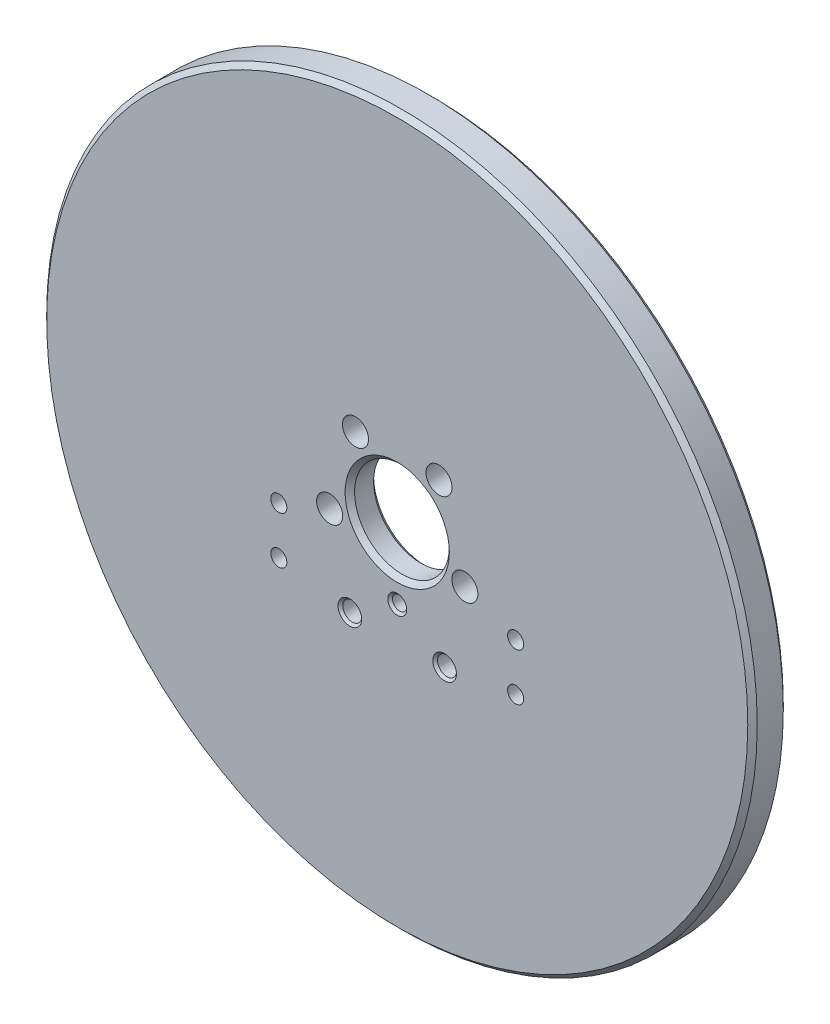
SolidWorks part; units mm, degrees
material "Q235"
ref_plane "前视基准面" through (0, 0, 0) normal (0, 0, 1) x (1, 0, 0)
ref_plane "上视基准面" through (0, 0, 0) normal (0, 1, 0) x (1, 0, 0)
ref_plane "右视基准面" through (0, 0, 0) normal (1, 0, 0) x (0, 0, -1)
ref_plane "基准面1" through (0, 0, 1) normal (0, 0, 1) x (1, 0, 0)
sketch "草图2" plane through (0, 0, 1) normal (0, 0, 1) x (1, 0, 0)
  circle A1 centre (18.5566, -25.5225) radius 150
  dimension "D1" = 300
extrude "凸台-拉伸1" add sketch "草图2" along normal blind 15
sketch "草图3" plane through (0, 0, 1) normal (0, 0, -1) x (-1, 0, 0)
  circle A0 centre (-18.5566, -25.5225) radius 35
  dimension "D1" = 70
extrude "切除-拉伸1" cut sketch "草图3" against normal blind 3
sketch "草图4" plane through (0, 0, 1) normal (0, 0, -1) x (-1, 0, 0)
  circle A0 centre (-18.5566, -25.5225) radius 35 construction
  circle A1 centre (-18.5566, -25.5225) radius 35
  circle A2 centre (-18.5566, -25.5225) radius 38.5
  dimension "D1" = 77
extrude "凸台-拉伸2" add sketch "草图4" along normal up to surface (16.5 mm away)
sketch "草图5" plane through (0, 0, 1) normal (0, 0, -1) x (-1, 0, 0)
  circle A0 centre (-18.5566, -25.5225) radius 38.5 construction
  circle A1 centre (-18.5566, -25.5225) radius 38.5
  circle A2 centre (-18.5566, -25.5225) radius 46.5
  dimension "D1" = 8
extrude "凸台-拉伸3" add sketch "草图5" along normal offset from surface (13.5 mm away) 3
chamfer "倒角1" distance 0.5 angle 45 2 edges at (18.5566, 12.9775, -15.5) (18.5566, 9.4775, -15.5)
hole_wizard "打孔尺寸根据内六角圆柱头螺钉的类型1" positions "草图8" profile "草图7" counterbore size "M6" standard "GB"
sketch "草图8" plane through (42.6264, -13.4634, 16) normal (0, 0, 1) x (1, 0, 0)
  line L0 (-24.0698, -12.0592) -> (-24.0698, 17.9408) construction
  line L2 (-24.0698, -12.0592) -> (-41.7034, 12.2114) construction
  line L3 (-24.0698, -12.0592) -> (-52.6015, -21.3297) construction
  line L6 (-24.0698, -12.0592) -> (4.4619, -21.3297) construction
  line L9 (-6.4362, 12.2114) -> (-24.0698, -12.0592) construction
  circle A0 centre (-24.0698, -12.0592) radius 30 construction
  circle A1 centre (-24.0698, -12.0592) radius 150 construction
  point P0 (-41.7034, 12.2114)
  point P45 (-6.4362, 12.2114)
  point P46 (4.4619, -21.3297)
  point P48 (-52.6015, -21.3297)
  point P50 (-24.0698, -42.0592) [skipped]
  dimension "D1" = 60
  dimension "D2" = 36
  dimension "D4" = 72
  dimension "D5" = 72
  dimension "D3" = 5
sketch "草图7" plane through (0.9231, -1.252, 16) normal (1, 0, 0) x (0, -1, 0)
  line L0 (0, 0) -> (0, 31.5)
  line L1 (0, 31.5) -> (3.3, 31.5)
  line L3 (3.3, 31.5) -> (3.3, 8)
  line L4 (3.3, 8) -> (5.5, 8)
  line L5 (5.5, 8) -> (5.5, 0)
  line L7 (5.5, 0) -> (0, 0)
  line L11 (0, -6.35) -> (0, 107.95) construction
  dimension "通孔孔直径" = 6.6
  dimension "通孔孔深度" = 31.5
  dimension "柱形沉头孔直径" = 11
  dimension "柱形沉头孔深度" = 8
hole_wizard "Ø6.0 (6) 直径孔1" positions "草图10" profile "草图9" hole size "Ø6.0" standard "ISO" end condition through all
sketch "草图10" plane through (0, 0, 16) normal (0, 0, 1) x (1, 0, 0)
  line L0 (-9.9751, -34.793) -> (47.0883, -34.793) construction
  line L2 (18.5566, -25.5225) -> (18.5566, -51.9555) construction
  circle A0 centre (18.5566, -25.5225) radius 30 construction
  circle A1 centre (18.5566, -25.5225) radius 150 construction
  point P0 (18.5566, -55.5225)
sketch "草图9" plane through (18.5566, -55.5225, 16) normal (1, 0, 0) x (0, -1, 0)
  line L0 (0, 0) -> (0, 31.5)
  line L1 (0, 31.5) -> (3, 31.5)
  line L2 (3, 31.5) -> (3, 0)
  line L5 (3, 0) -> (0, 0)
  line L11 (0, -6.35) -> (0, 107.95) construction
  dimension "通孔孔直径" = 6
  dimension "通孔孔深度" = 31.5
chamfer "倒角3" distance 1 angle 45 1 edges at (21.5566, -55.5225, 16)
ref_plane "基准面2" through (0, 0, 11) normal (0, 0, -1) x (-1, 0, 0)
sketch "草图20" plane through (0, 0, 1) normal (0, 0, -1) x (-1, 0, 0)
  circle A0 centre (-18.5566, -25.5225) radius 46.5 construction
  circle A1 centre (-18.5566, -25.5225) radius 46.5
extrude "切除-拉伸5" cut sketch "草图20" along normal blind 69
sketch "草图22" plane through (0, 0, 16) normal (0, 0, 1) x (1, 0, 0)
  line L0 (0.9231, -1.252) -> (36.1902, -1.252) construction
  line L1 (18.5566, -25.5225) -> (50.0448, -25.5225) construction
  line L2 (18.5566, -25.5225) -> (18.5566, 3.016) construction
  line L3 (18.5566, -25.5225) -> (18.5566, -68.5225) construction
  line L4 (38.5566, -68.5225) -> (-1.4434, -68.5225) construction
  circle A0 centre (-1.4434, -68.5225) radius 4
  circle A1 centre (38.5566, -68.5225) radius 4
  circle A2 centre (18.5566, -25.5225) radius 150 construction
  dimension "D1" = 8
  dimension "D2" = 40
  dimension "D4" = 43
extrude "切除-拉伸7" cut sketch "草图22" against normal through all
chamfer "倒角6" distance 1 angle 45 2 edges at (42.5566, -68.5225, 16) (2.5566, -68.5225, 16)
hole_wizard "M8 螺纹孔1" positions "草图24" profile "草图23" tap size "M8" standard "GB" end condition through all
sketch "草图24" plane through (0, 0, 16) normal (0, 0, 1) x (1, 0, 0)
  circle A0 centre (18.5566, -25.5225) radius 150 construction
  point P1 (-31.4434, -43.5225)
  point P3 (-31.4434, -63.5225)
  point P5 (68.5566, -43.5225)
  point P7 (68.5566, -63.5225)
  point P10 (18.5566, -25.5225)
  dimension "D4" = 50
  dimension "D1" = 18
  dimension "D2" = 20
  dimension "D3" = 100
cosmetic thread "孔螺蚊线2" parameters "D2"=8
cosmetic thread "孔螺蚊线3" parameters "D2"=8
cosmetic thread "孔螺蚊线4" parameters "D2"=8
cosmetic thread "孔螺蚊线5" parameters "D2"=8
sketch "草图23" plane through (-31.4434, -43.5225, 16) normal (1, 0, 0) x (0, -1, 0)
  line L0 (0, 0) -> (0, 15)
  line L1 (0, 15) -> (3.4, 15)
  line L2 (3.4, 15) -> (3.4, 0)
  line L5 (3.4, 0) -> (0, 0)
  line L11 (0, -6.35) -> (0, 107.95) construction
  dimension "通孔螺纹孔钻头直径" = 6.8
  dimension "通孔螺纹孔钻头深度" = 15
cosmetic thread "孔螺蚊线6" parameters "D2"=8
sketch "草图27" plane through (0, 0, 1) normal (0, 0, -1) x (-1, 0, 0)
  circle A0 centre (-18.5566, -25.5225) radius 40
  circle A1 centre (-18.5566, -25.5225) radius 35 construction
  circle A2 centre (-18.5566, -25.5225) radius 35
  dimension "D1" = 80
extrude "凸台-拉伸4" add sketch "草图27" along normal blind 5
chamfer "倒角7" distance 0.5 angle 45 1 edges at (-16.4434, -25.5225, -4)
chamfer "倒角8" distance 2 angle 45 2 edges at (168.5566, -25.5225, 1) (168.5566, -25.5225, 16)
sketch "草图25" plane through (0, 0, 16) normal (0, 0, 1) x (1, 0, 0)
  circle A0 centre (18.5566, -25.5225) radius 20
  dimension "D1" = 40
extrude "切除-拉伸8" cut sketch "草图25" against normal through all
chamfer "倒角9" distance 2 angle 45 2 edges at (-1.4434, -25.5225, 4) (38.5566, -25.5225, 16)
fillet "圆角1" radius 1 1 edges at (58.5566, -25.5225, 1)
sketch "草图28" plane through (0, 0, 16) normal (0, 0, 1) x (1, 0, 0)
  circle A0 centre (18.5566, -25.5225) radius 110
  dimension "D1" = 220
extrude "切除-拉伸9" [suppressed] cut sketch "草图28" against normal through all flip side to cut
sketch "草图29" [suppressed] plane through (0, 0, 16) normal (0, 0, 1) x (1, 0, 0)
  line L1 (-71.4434, -82.1836) -> (108.5566, -82.1836)
  line L2 (-71.4434, -82.1836) -> (-71.4434, -280.5225)
  line L3 (-71.4434, -280.5225) -> (108.5566, -280.5225)
  line L4 (108.5566, -82.1836) -> (108.5566, -280.5225)
  circle A0 centre (18.5566, -25.5225) radius 110 construction
  circle A1 centre (18.5566, -25.5225) radius 22 construction
  dimension "D1" = 180
  dimension "D2" = 90
  dimension "D3" = 255
extrude "凸台-拉伸5" [suppressed] add sketch "草图29" against normal up to surface (15 mm away)
